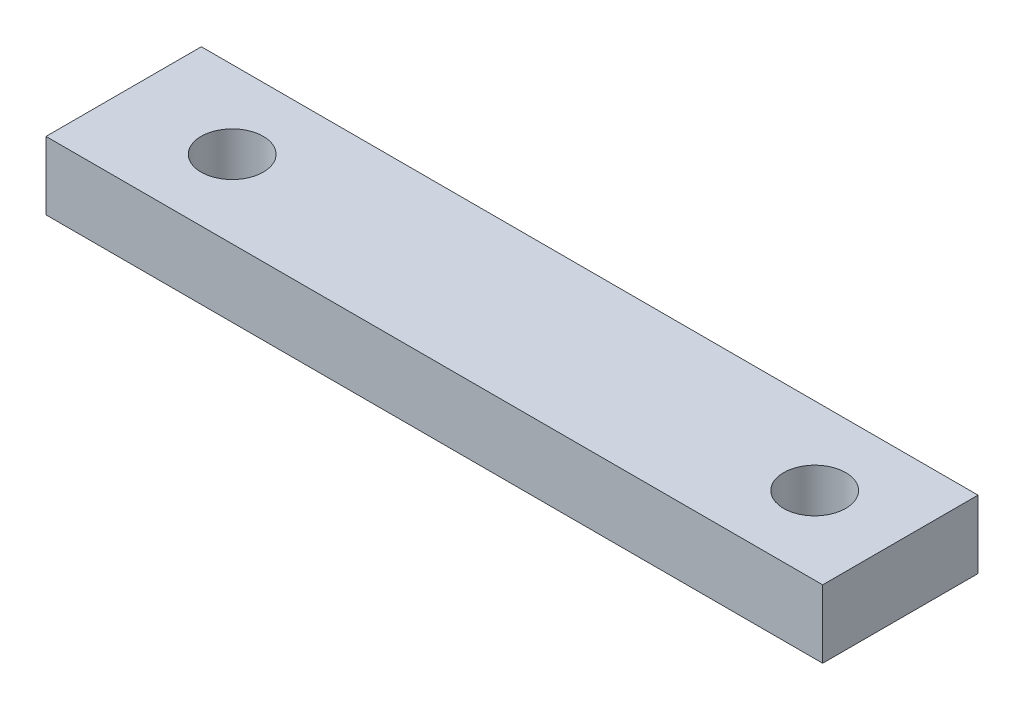
SolidWorks part; units mm, degrees
ref_plane "前视基准面" through (0, 0, 0) normal (0, 0, 1) x (1, 0, 0)
ref_plane "上视基准面" through (0, 0, 0) normal (0, 1, 0) x (1, 0, 0)
ref_plane "右视基准面" through (0, 0, 0) normal (1, 0, 0) x (0, 0, -1)
other "Configuration Table"
sketch "草图1" plane through (0, 0, 0) normal (0, 1, 0) x (1, 0, 0)
  line L1 (-20, -4) -> (20, -4)
  line L2 (-20, -4) -> (-20, 4)
  line L3 (-20, 4) -> (20, 4)
  line L4 (20, -4) -> (20, 4)
  line L5 (-20, -4) -> (20, 4) construction
  line L6 (-20, 4) -> (20, -4) construction
  circle A0 centre (-14.8485, 0) radius 1.6
  circle A1 centre (15.1515, 0) radius 1.6
  point P0 (0, 0)
  point P10 (14.6926, 0)
  point P11 (-14.8485, 0)
  dimension "D3" = 30
  dimension "D1" = 8
  dimension "D2" = 40
extrude "凸台-拉伸2" add sketch "草图1" along normal blind 3.5 contours L2 L1 L4 L3
sketch "草图4" plane through (0, 0, 0) normal (0, -1, 0) x (1, 0, 0)
  circle A0 centre (-14.4108, 0) radius 1.6
  circle A1 centre (15.5892, 0) radius 1.6
  point P4 (15.024, 0)
  dimension "D1" = 30
extrude "切除-拉伸1" cut sketch "草图4" against normal blind 3.5
